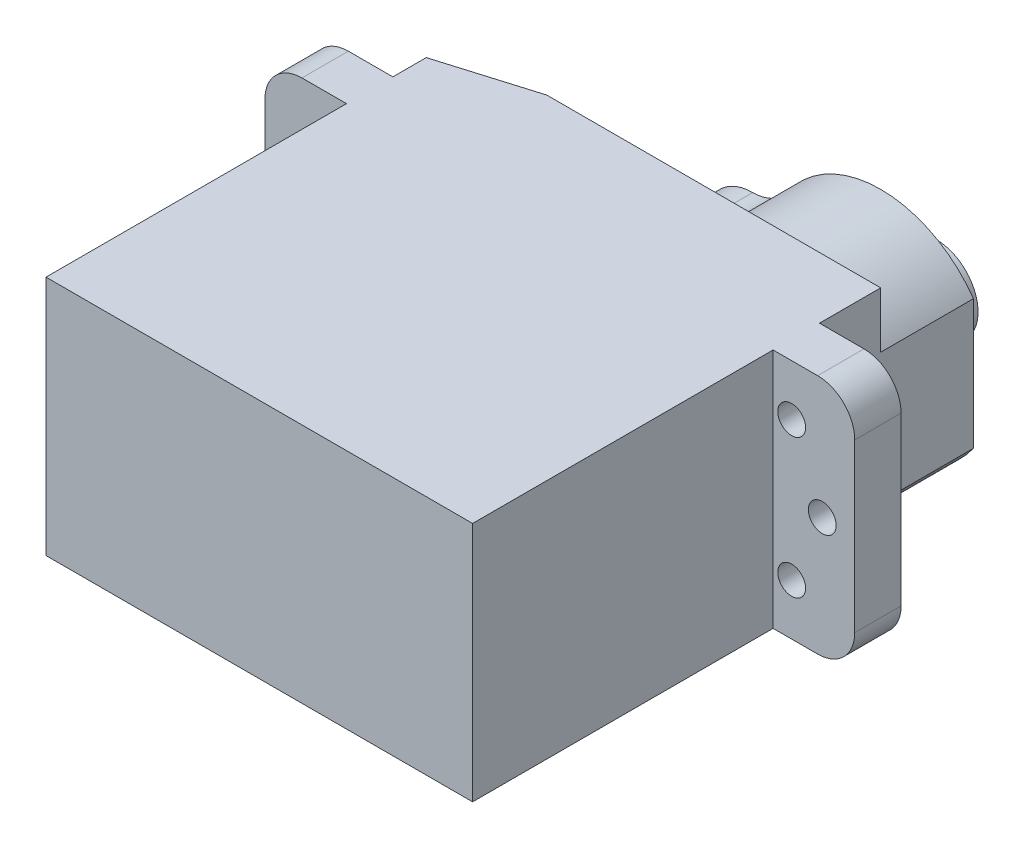
SolidWorks part; units mm, degrees
material "Nylon 101"
ref_plane "Front Plane" through (0, 0, 0) normal (0, 0, 1) x (1, 0, 0)
ref_plane "Top Plane" through (0, 0, 0) normal (0, 1, 0) x (1, 0, 0)
ref_plane "Right Plane" through (0, 0, 0) normal (1, 0, 0) x (0, 0, -1)
sketch "Sketch1" plane through (0, 0, 0) normal (0, 1, 0) x (1, 0, 0)
  line L0 (0, 20.5) -> (5, 22)
  line L1 (0, 0) -> (23, 0)
  line L2 (0, 0) -> (0, 16.2)
  line L3 (11.5, 22) -> (23, 22)
  line L4 (23, 0) -> (23, 16.2)
  line L5 (5, 22) -> (11.5, 22)
  line L6 (23, 22) -> (23, 18.7)
  line L7 (11.5, 0) -> (11.5, 33.6349) construction
  line L8 (0, 18.7) -> (-4.4, 18.7)
  line L9 (-4.4, 18.7) -> (-4.4, 16.2)
  line L10 (-4.4, 16.2) -> (0, 16.2)
  line L11 (27.4, 16.2) -> (23, 16.2)
  line L12 (27.4, 18.7) -> (27.4, 16.2)
  line L13 (23, 18.7) -> (27.4, 18.7)
  line L14 (0, 18.7) -> (0, 20.5)
  dimension "D1" = 20.5
  dimension "D2" = 23
  dimension "D3" = 5
  dimension "D4" = 22
  dimension "D5" = 2.5
  dimension "D6" = 1.8
  dimension "D7" = 31.8
extrude "Boss-Extrude1" add sketch "Sketch1" along normal blind 13
sketch "Sketch2" plane through (0, 0, -22) normal (0, 0, -1) x (-1, 0, 0)
  line L0 (-23, 6.5) -> (10.7503, 6.5) construction
  line L1 (-23, 13) -> (-23, 0) construction
  line L2 (-23, 9.9943) -> (-23, 3.0057)
  arc A0 (-23, 3.0057) -> (-12.9967, 3.0104) centre (-18, 6.5) ccw
  arc A1 (-11.1, 4) -> (-11.1, 9) centre (-11.1, 6.5) ccw
  arc A2 (-11.1, 9) -> (-12.9967, 9.9896) centre (-11.1, 11.3125) cw
  arc A3 (-11.1, 4) -> (-12.9967, 3.0104) centre (-11.1, 1.6875) ccw
  arc A4 (-12.9967, 9.9896) -> (-23, 9.9943) centre (-18, 6.5) ccw
  dimension "D2" = 12.2
  dimension "D3" = 5
  dimension "D4" = 11.9
  dimension "D1" = 5
extrude "Boss-Extrude2" add sketch "Sketch2" along normal blind 5
fillet "Fillet1" radius 2 4 edges at (-4.4, 13, -17.45) (-4.4, 0, -17.45) (27.4, 13, -17.45) (27.4, 0, -17.45)
sketch "Sketch3" plane through (0, 0, -18.7) normal (0, 0, -1) x (-1, 0, 0)
  line L0 (-27.4, 6.5) -> (-23, 6.5) construction
  line L1 (-27.4, 11) -> (-27.4, 2) construction
  line L2 (-23, 9.9943) -> (-23, 3.0057) construction
  line L3 (-25.4, 13) -> (-23, 13) construction
  line L4 (-25.4, 13) -> (2.4, 13) construction
  line L5 (-11.5, 13) -> (-11.5, -0.9512) construction
  circle A0 centre (-25.65, 6.5) radius 0.75
  circle A1 centre (-24, 10.25) radius 0.75
  circle A2 centre (-24, 2.75) radius 0.75
  circle A3 centre (1, 2.75) radius 0.75
  circle A4 centre (2.65, 6.5) radius 0.75
  circle A5 centre (1, 10.25) radius 0.75
  dimension "D1" = 1.5
  dimension "D2" = 28.3
  dimension "D3" = 1.5
  dimension "D4" = 2.75
  dimension "D5" = 25
extrude "Cut-Extrude1" cut sketch "Sketch3" against normal blind 4.9
sketch "Sketch4" plane through (0, 0, -27) normal (0, 0, -1) x (-1, 0, 0)
  circle A0 centre (-18, 6.5) radius 2.25
  dimension "D1" = 4.5
extrude "Boss-Extrude3" add sketch "Sketch4" along normal blind 3
